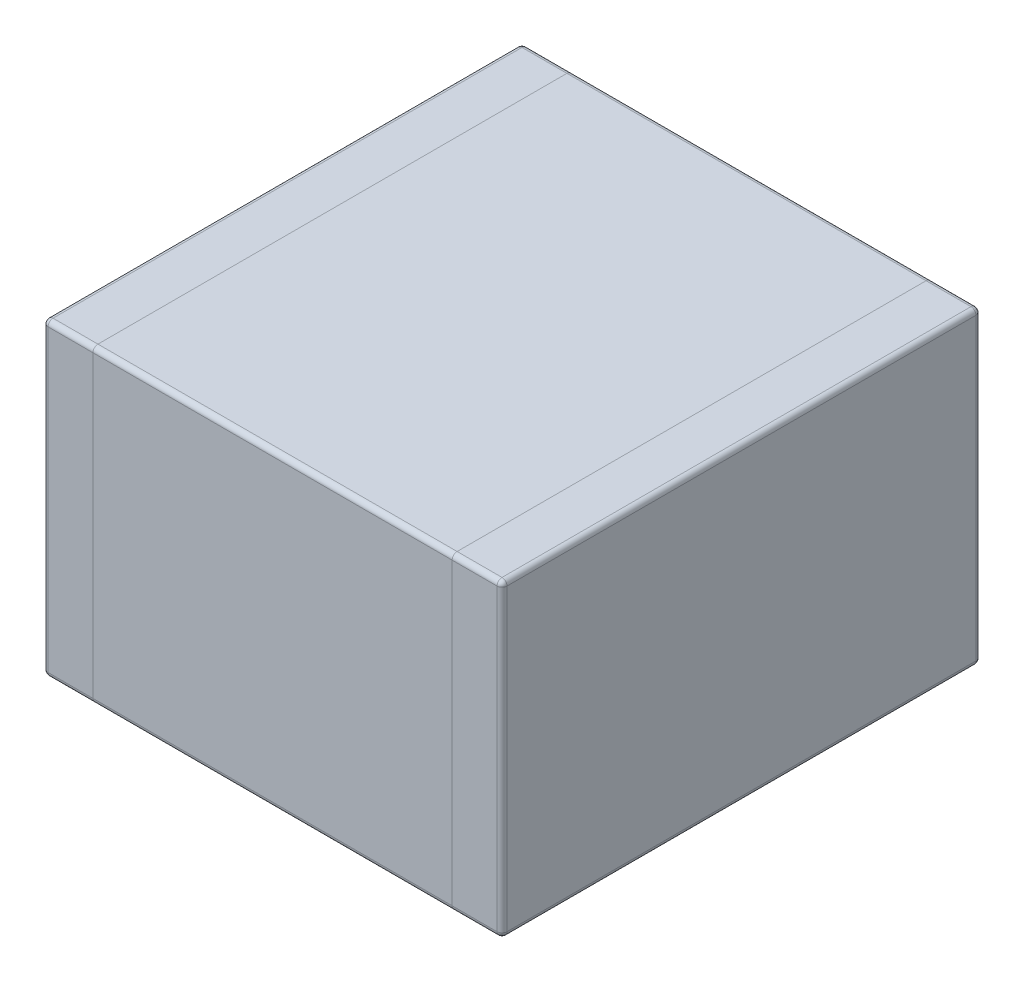
SolidWorks part; units mm, degrees
ref_plane "Front Plane" through (0, 0, 0) normal (0, 0, 1) x (1, 0, 0)
ref_plane "Top Plane" through (0, 0, 0) normal (0, 1, 0) x (1, 0, 0)
ref_plane "Right Plane" through (0, 0, 0) normal (1, 0, 0) x (0, 0, -1)
sketch "Sketch1" plane through (0, 0, 0) normal (0, 1, 0) x (1, 0, 0)
  line L1 (-2.3, -2.4) -> (2.3, -2.4)
  line L2 (-2.3, -2.4) -> (-2.3, 2.4)
  line L3 (-2.3, 2.4) -> (2.3, 2.4)
  line L4 (2.3, -2.4) -> (2.3, 2.4)
  line L5 (-2.3, -2.4) -> (2.3, 2.4) construction
  line L6 (-2.3, 2.4) -> (2.3, -2.4) construction
  point P0 (0, 0)
  dimension "D1" = 4.6
  dimension "D2" = 4.8
extrude "Extrude1" add sketch "Sketch1" along normal blind 3.1
fillet "Fillet1" radius 0.05 12 edges at (2.3, 1.55, -2.4) (-2.3, 1.55, -2.4) (-2.3, 1.55, 2.4) (2.3, 1.55, 2.4) (0, 3.1, 2.4) (-2.3, 3.1, 0) (0, 3.1, -2.4) (2.3, 3.1, 0) (0, 0, -2.4) (-2.3, 0, 0) (0, 0, 2.4) (2.3, 0, 0)
sketch "Sketch2" plane through (0, 0, 0) normal (0, 1, 0) x (1, 0, 0)
  line L0 (-2.25, 2.4) -> (2.25, 2.4) construction
  line L1 (-1.8, -2.4) -> (1.8, -2.4)
  line L2 (-1.8, -2.4) -> (-1.8, 2.4)
  line L3 (-1.8, 2.4) -> (1.8, 2.4)
  line L4 (1.8, -2.4) -> (1.8, 2.4)
  line L5 (2.25, -2.4) -> (-2.25, -2.4) construction
  line L6 (0, 2.35) -> (0, -0.6635) construction
  line L7 (2.25, 2.35) -> (-2.25, 2.35) construction
  line L9 (-2.3, -2.35) -> (-2.3, 2.35) construction
  dimension "D1" = 0.5
split line "Split Line3"
